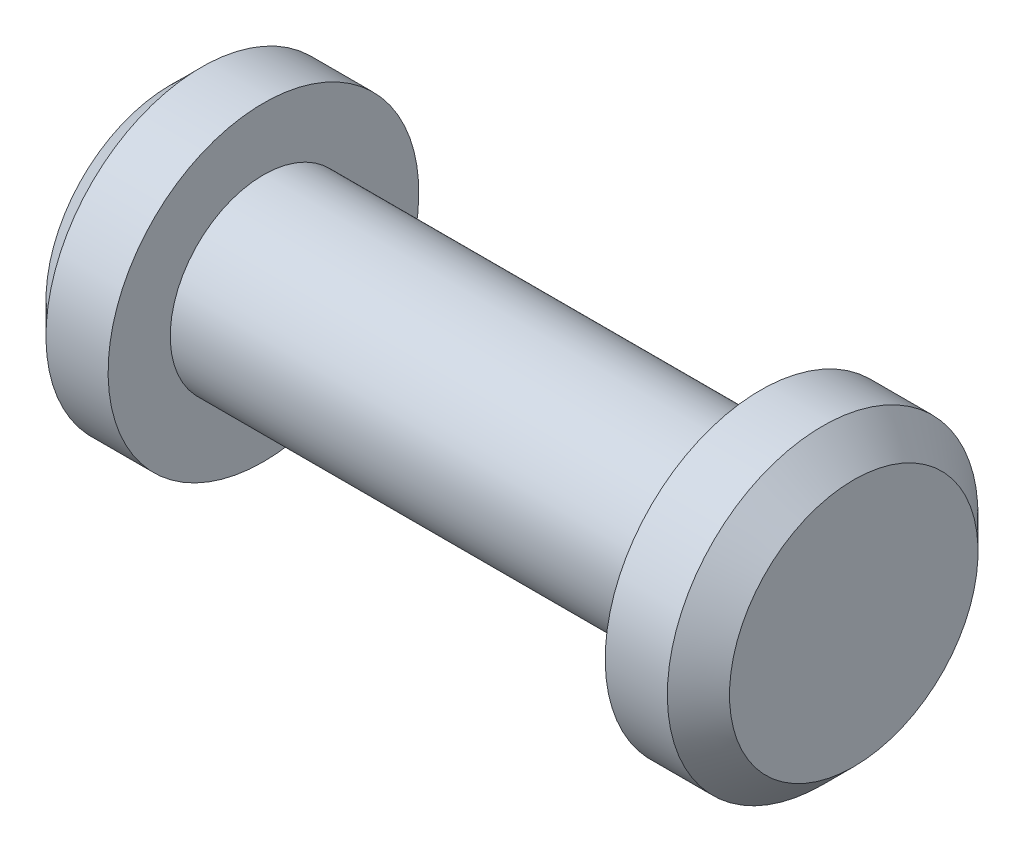
SolidWorks part; units mm, degrees
ref_plane "Front" through (0, 0, 0) normal (0, 0, 1) x (1, 0, 0)
ref_plane "Top" through (0, 0, 0) normal (0, 1, 0) x (1, 0, 0)
ref_plane "Right" through (0, 0, 0) normal (1, 0, 0) x (0, 0, -1)
sketch "Esquisse1" plane through (0, 0, 0) normal (0, 0, 1) x (1, 0, 0)
  line L0 (-11, 0) -> (11, 0)
  line L1 (11, 0) -> (11, -4)
  line L2 (11, -4) -> (10, -5)
  line L3 (10, -5) -> (8, -5)
  line L4 (8, -5) -> (8, -3)
  line L5 (8, -3) -> (-8, -3)
  line L6 (0, 0) -> (0, -9.3254) construction
  line L7 (-8, -5) -> (-8, -3)
  line L8 (-10, -5) -> (-8, -5)
  line L9 (-11, -4) -> (-10, -5)
  line L10 (-11, 0) -> (-11, -4)
  point P10 (0, -3)
  dimension "D1" = 5
  dimension "D2" = 3
  dimension "D3" = 1
  dimension "D4" = 1
  dimension "D5" = 2
  dimension "D7" = 16
revolve "Révolution1" add sketch "Esquisse1" angle 360 about L0
